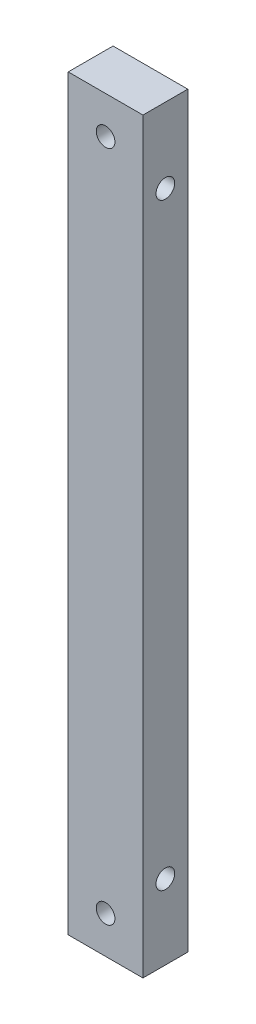
SolidWorks part; units mm, degrees
ref_plane "Front Plane" through (0, 0, 0) normal (0, 0, 1) x (1, 0, 0)
ref_plane "Top Plane" through (0, 0, 0) normal (0, 1, 0) x (1, 0, 0)
ref_plane "Right Plane" through (0, 0, 0) normal (1, 0, 0) x (0, 0, -1)
ref_plane "Plane1" through (0, 0, 6) normal (0, 0, 1) x (1, 0, 0)
sketch "Sketch1" plane through (0, 0, 6) normal (0, 0, 1) x (1, 0, 0)
  line L0 (5, 50) -> (-5, 50)
  line L1 (-5, 50) -> (-5, -50)
  line L2 (-5, -50) -> (5, -50)
  line L3 (5, -50) -> (5, 50)
extrude "Boss-Extrude1" add sketch "Sketch1" against normal blind 6
hole_wizard "Ø2.5 (2.5) Diameter Hole1" positions "Sketch3" profile "Sketch2" hole size "Ø2.5" standard "ANSI Metric"
sketch "Sketch3" plane through (0, 0, 6) normal (0, 0, 1) x (1, 0, 0)
  point P0 (0, 45)
  point P1 (0, -45)
sketch "Sketch2" plane through (0, 45, 6) normal (1, 0, 0) x (0, -1, 0)
  line L0 (0, 0) -> (0, 6)
  line L1 (0, 6) -> (1.25, 6)
  line L2 (1.25, 6) -> (1.25, 0)
  line L5 (1.25, 0) -> (0, 0)
  line L11 (0, -6.35) -> (0, 107.95) construction
  dimension "Thru Hole Dia." = 2.5
  dimension "Thru Hole Depth" = 6
hole_wizard "Ø2.5 (2.5) Diameter Hole2" positions "Sketch5" profile "Sketch4" hole size "Ø2.5" standard "ANSI Metric"
sketch "Sketch5" plane through (5, 0, 0) normal (1, 0, 0) x (0, 0, -1)
  point P0 (-3, 40)
  point P1 (-3, -40)
sketch "Sketch4" plane through (5, 40, 3) normal (0, 1, 0) x (0, 0, -1)
  line L0 (0, 0) -> (0, 10)
  line L1 (0, 10) -> (1.25, 10)
  line L2 (1.25, 10) -> (1.25, 0)
  line L5 (1.25, 0) -> (0, 0)
  line L11 (0, -6.35) -> (0, 107.95) construction
  dimension "Thru Hole Dia." = 2.5
  dimension "Thru Hole Depth" = 10
